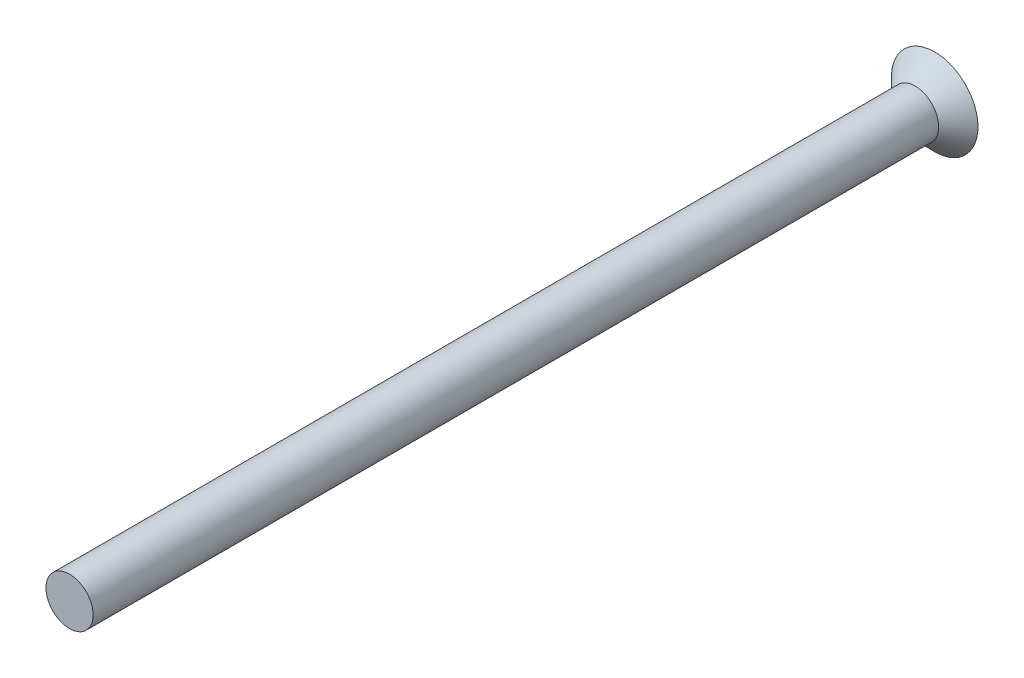
SolidWorks part; units mm, degrees
ref_plane "前视基准面" through (0, 0, 0) normal (0, 0, 1) x (1, 0, 0)
ref_plane "上视基准面" through (0, 0, 0) normal (0, 1, 0) x (1, 0, 0)
ref_plane "右视基准面" through (0, 0, 0) normal (1, 0, 0) x (0, 0, -1)
other "Configuration Table"
sketch "草图1" plane through (0, 0, 0) normal (0, 0, 1) x (1, 0, 0)
  circle A1 centre (0, 0) radius 1.5
extrude "M3简化螺杆_沉头总长55mm" add sketch "草图1" along normal blind 53.75 from offset 1.25
sketch "草图2" plane through (0, 0, 0) normal (0, 0, 1) x (1, 0, 0)
  circle A0 centre (0, 0) radius 2.75
extrude "M3沉头_D5p5_90度" add sketch "草图2" along normal blind 1.25 draft 45
